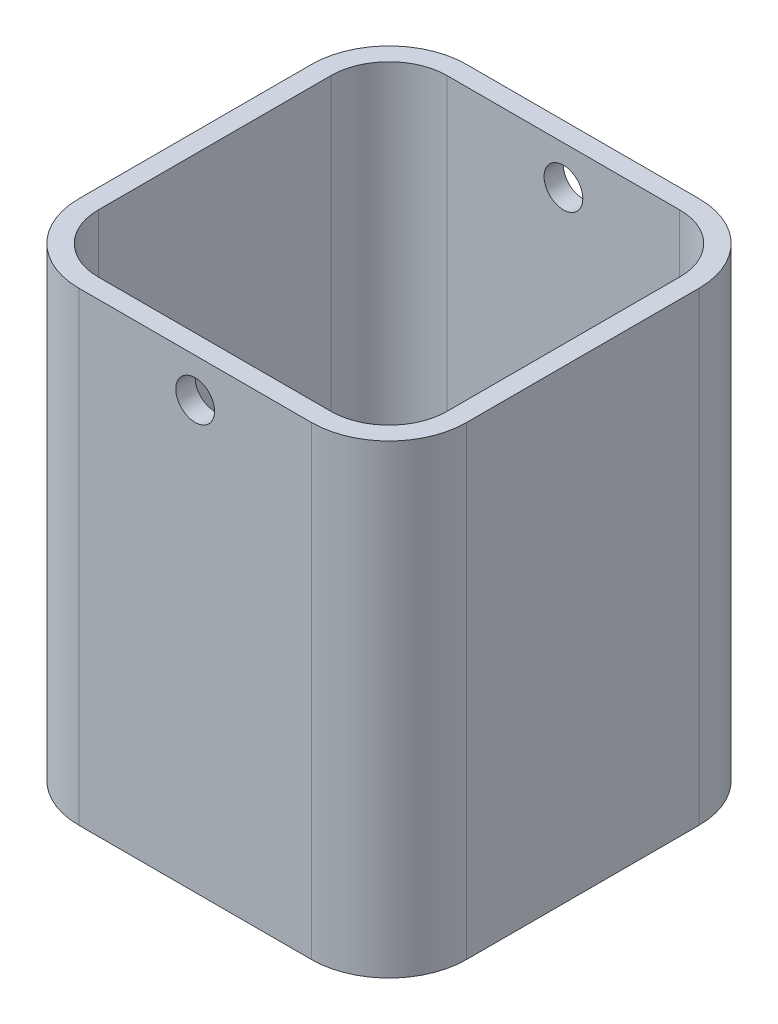
SolidWorks part; units mm, degrees
ref_plane "Front Plane" through (0, 0, 0) normal (0, 0, 1) x (1, 0, 0)
ref_plane "Top Plane" through (0, 0, 0) normal (0, 1, 0) x (1, 0, 0)
ref_plane "Right Plane" through (0, 0, 0) normal (1, 0, 0) x (0, 0, -1)
sketch "Sketch1" plane through (0, 0, 0) normal (0, 1, 0) x (1, 0, 0)
  line L1 (0, 0) -> (50, 0)
  line L2 (0, 0) -> (0, 50)
  line L3 (0, 50) -> (50, 50)
  line L4 (50, 0) -> (50, 50)
  dimension "D1" = 50
  dimension "D2" = 50
extrude "Boss-Extrude1" add sketch "Sketch1" along normal blind 60
fillet "Fillet1" radius 10 4 edges at (0, 30, -50) (50, 30, -50) (50, 30, 0) (0, 30, 0)
shell "Shell1" thickness 2.5
sketch "Sketch2" plane through (0, 0, 0) normal (0, 0, 1) x (1, 0, 0)
  line L0 (0, 0) -> (0, 60) construction
  line L1 (10, 60) -> (40, 60) construction
  circle A0 centre (25, 55) radius 2.5
  dimension "D2" = 5
  dimension "D1" = 25
  dimension "D3" = 5
extrude "Cut-Extrude1" cut sketch "Sketch2" against normal through all
equation "\"w50\"=10"
